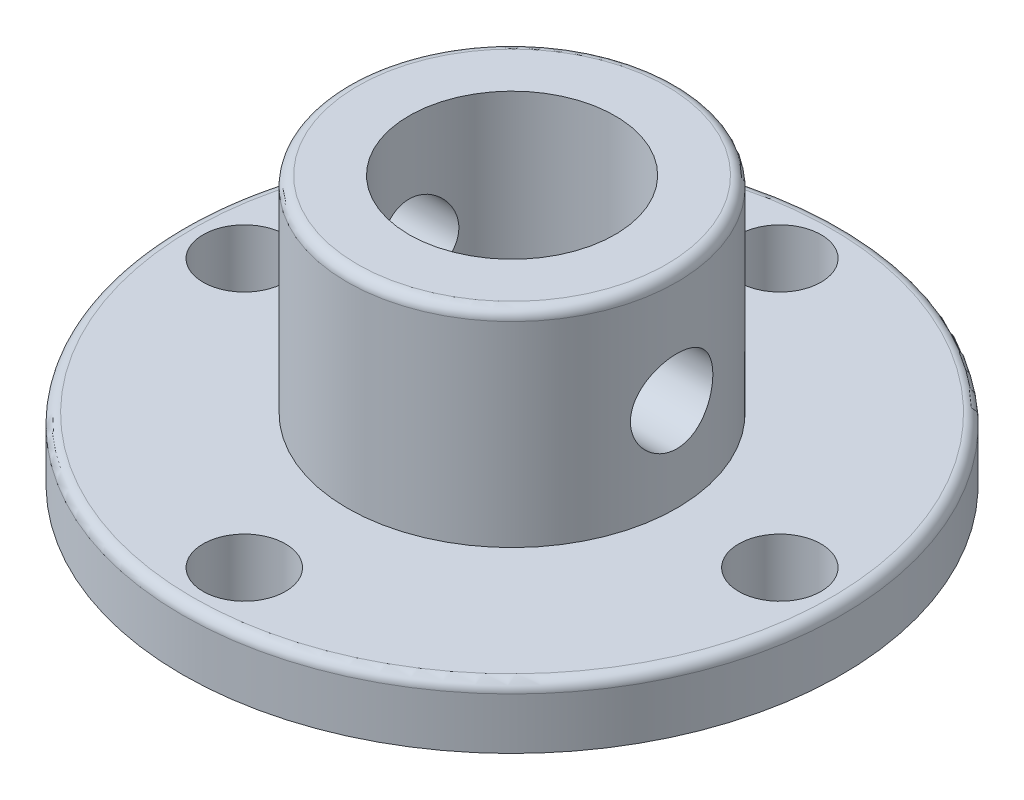
SolidWorks part; units mm, degrees
ref_plane "前视基准面" through (0, 0, 0) normal (0, 0, 1) x (1, 0, 0)
ref_plane "上视基准面" through (0, 0, 0) normal (0, 1, 0) x (1, 0, 0)
ref_plane "右视基准面" through (0, 0, 0) normal (1, 0, 0) x (0, 0, -1)
sketch "草图1" plane through (0, 0, 0) normal (0, 1, 0) x (1, 0, 0)
  circle A0 centre (0, 0) radius 16
  dimension "D1" = 32
extrude "凸台-拉伸1" add sketch "草图1" along normal blind 3
sketch "草图2" plane through (0, 3, 0) normal (0, 1, 0) x (1, 0, 0)
  circle A0 centre (0, 0) radius 8
  dimension "D1" = 16
extrude "凸台-拉伸2" add sketch "草图2" along normal blind 10
sketch "草图3" plane through (0, 13, 0) normal (0, 1, 0) x (1, 0, 0)
  circle A0 centre (0, 0) radius 5
  dimension "D1" = 10
extrude "切除-拉伸1" cut sketch "草图3" against normal through all
sketch "草图4" plane through (0, 3, 0) normal (0, 1, 0) x (1, 0, 0)
  circle A0 centre (0, 0) radius 13 construction
  circle A1 centre (0, 13) radius 2
  circle A2 centre (-13, 0) radius 2
  circle A3 centre (0, -13) radius 2
  circle A4 centre (13, 0) radius 2
  dimension "D1" = 26
extrude "切除-拉伸2" cut sketch "草图4" against normal blind 7
sketch "草图5" plane through (0, 0, 0) normal (1, 0, 0) x (0, 0, -1)
  line L0 (-16, 0) -> (16, 0) construction
  circle A0 centre (0, 7.5) radius 2
  dimension "D1" = 7.5
extrude "切除-拉伸3" cut sketch "草图5" against normal through all and the other way through all
fillet "圆角1" radius 0.5 1 edges at (0, 3, 16)
fillet "圆角2" radius 0.5 1 edges at (0, 13, 8)
